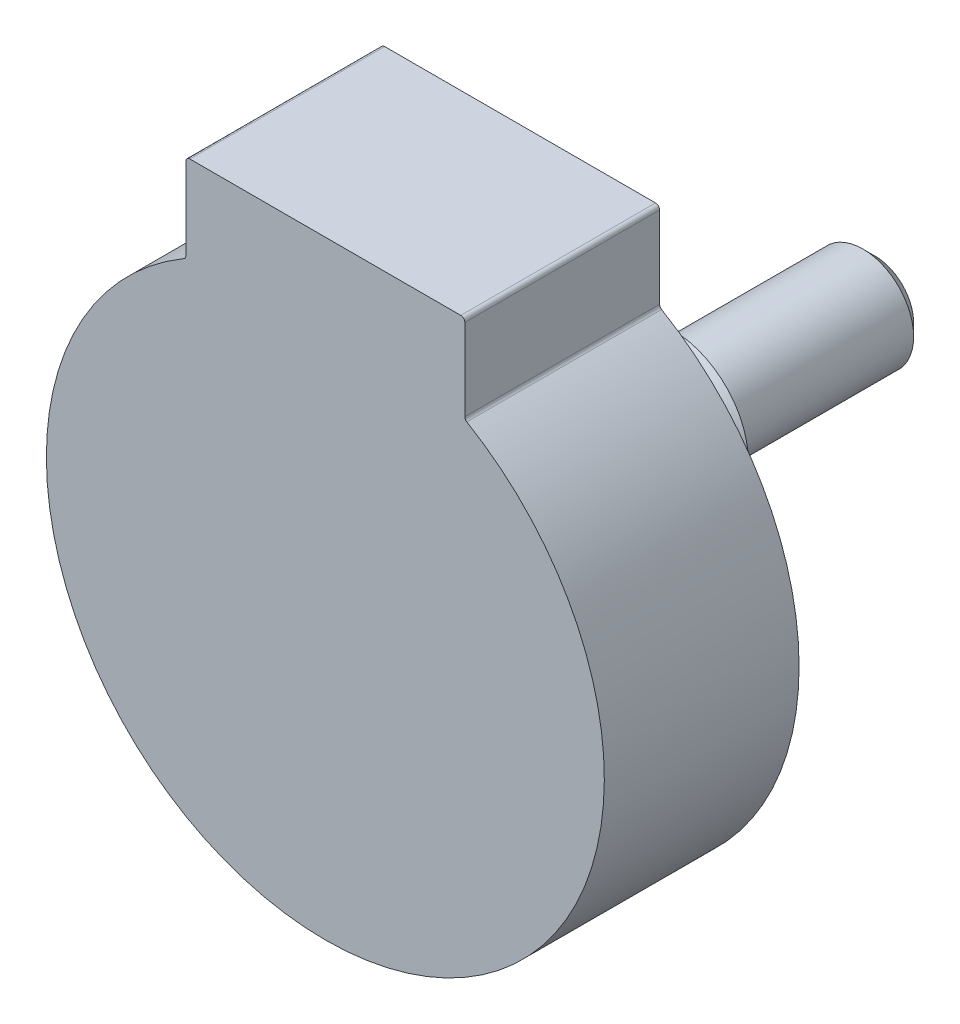
SolidWorks part; units mm, degrees
ref_plane "Front Plane" through (0, 0, 0) normal (0, 0, 1) x (1, 0, 0)
ref_plane "Top Plane" through (0, 0, 0) normal (0, 1, 0) x (1, 0, 0)
ref_plane "Right Plane" through (0, 0, 0) normal (1, 0, 0) x (0, 0, -1)
sketch "Sketch1" plane through (0, 0, 0) normal (0, 0, 1) x (1, 0, 0)
  line L0 (-8.7312, 15.123) -> (-8.7312, 20.6375)
  line L1 (-8.7312, 20.6375) -> (8.7312, 20.6375)
  line L2 (8.7312, 20.6375) -> (8.7312, 15.123)
  arc A0 (-8.7312, 15.123) -> (8.7312, 15.123) centre (0, 0) ccw
  point P6 (0, 20.6375)
  dimension "D1" = 34.925
  dimension "D2" = 17.4625
  dimension "D3" = 20.6375
extrude "Extrude1" add sketch "Sketch1" along normal blind 12.192
sketch "Sketch3" plane through (0, 0, 0) normal (0, 0, -1) x (-1, 0, 0)
  line L1 (3.175, 1.8331) -> (0, 3.6662)
  line L2 (0, 3.6662) -> (-3.175, 1.8331)
  line L3 (-3.175, 1.8331) -> (-3.175, -1.8331)
  line L4 (-3.175, -1.8331) -> (0, -3.6662)
  line L5 (0, -3.6662) -> (3.175, -1.8331)
  line L6 (3.175, -1.8331) -> (3.175, 1.8331)
  circle A0 centre (0, 0) radius 3.175 construction
  dimension "D1" = 6.35
extrude "Extrude3" add sketch "Sketch3" along normal blind 1.27 separate body
sketch "Sketch5" plane through (0, 0, 0) normal (0, 1, 0) x (1, 0, 0)
  line L0 (0, 0) -> (0, 22.225)
  line L1 (0, 22.225) -> (3.1686, 22.225)
  line L2 (3.1686, 22.225) -> (3.1687, 9.525)
  line L3 (3.1687, 9.525) -> (4.7625, 9.525)
  line L4 (4.7625, 9.525) -> (4.318, 9.1281)
  line L5 (4.318, 9.1281) -> (4.7625, 8.7313)
  line L6 (4.7625, 8.7313) -> (4.318, 8.3344)
  line L7 (4.318, 8.3344) -> (4.7625, 7.9375)
  line L8 (4.7625, 7.9375) -> (4.318, 7.5406)
  line L9 (4.318, 7.5406) -> (4.7625, 7.1438)
  line L10 (4.7625, 7.1438) -> (4.318, 6.7469)
  line L11 (4.318, 6.7469) -> (4.7625, 6.35)
  line L12 (4.7625, 6.35) -> (4.318, 5.9531)
  line L13 (4.318, 5.9531) -> (4.7625, 5.5563)
  line L14 (4.7625, 5.5563) -> (4.318, 5.1594)
  line L15 (4.318, 5.1594) -> (4.7625, 4.7625)
  line L16 (4.7625, 4.7625) -> (4.318, 4.3656)
  line L17 (4.318, 4.3656) -> (4.7625, 3.9688)
  line L18 (4.7625, 3.9688) -> (4.318, 3.5719)
  line L19 (4.318, 3.5719) -> (4.7625, 3.175)
  line L20 (4.7625, 3.175) -> (4.318, 2.7781)
  line L21 (4.318, 2.7781) -> (4.7625, 2.3813)
  line L22 (4.7625, 2.3813) -> (4.318, 1.9844)
  line L23 (4.318, 1.9844) -> (4.7625, 1.5875)
  line L24 (4.7625, 1.5875) -> (4.318, 1.1906)
  line L25 (4.318, 1.1906) -> (4.7625, 0.7938)
  line L26 (4.7625, 0.7938) -> (4.318, 0.3969)
  line L27 (4.318, 0.3969) -> (4.7625, 0)
  line L28 (0, 0) -> (3.175, 0) construction
  line L29 (8.7312, 0) -> (-8.7312, 0) construction
  line L30 (4.7625, 0) -> (0, 0)
  dimension "D1" = 3.1686
  dimension "D2" = 4.7625
  dimension "D3" = 0.7937
  dimension "D4" = 0.3969
  dimension "D5" = 4.318
  dimension "D6" = 12.7
  dimension "D7" = 9.525
  dimension "D8" = 11
revolve "Revolve1" add sketch "Sketch5" angle 360 about L0
chamfer "Chamfer1" distance 0.762 angle 45 1 edges at (3.1686, 0, -22.225)
fillet "Fillet1" radius 0.254 4 edges at (-8.7312, 20.6375, 6.096) (-8.7312, 15.123, 6.096) (8.7312, 15.123, 6.096) (8.7312, 20.6375, 6.096)
sketch "Sketch6" plane through (0, 0, 0) normal (0, 0, -1) x (-1, 0, 0)
  arc A0 (17.1739, 3.1619) -> (17.1739, -3.1619) centre (17.4625, 0) ccw
  arc A1 (-8.8564, 15.05) -> (8.8564, 15.05) centre (0, 0) ccw construction
  arc A2 (17.1739, -3.1619) -> (17.1739, 3.1619) centre (0, 0) ccw
  dimension "D1" = 6.35
extrude "Boss-Extrude1" add sketch "Sketch6" along normal blind 1.905
